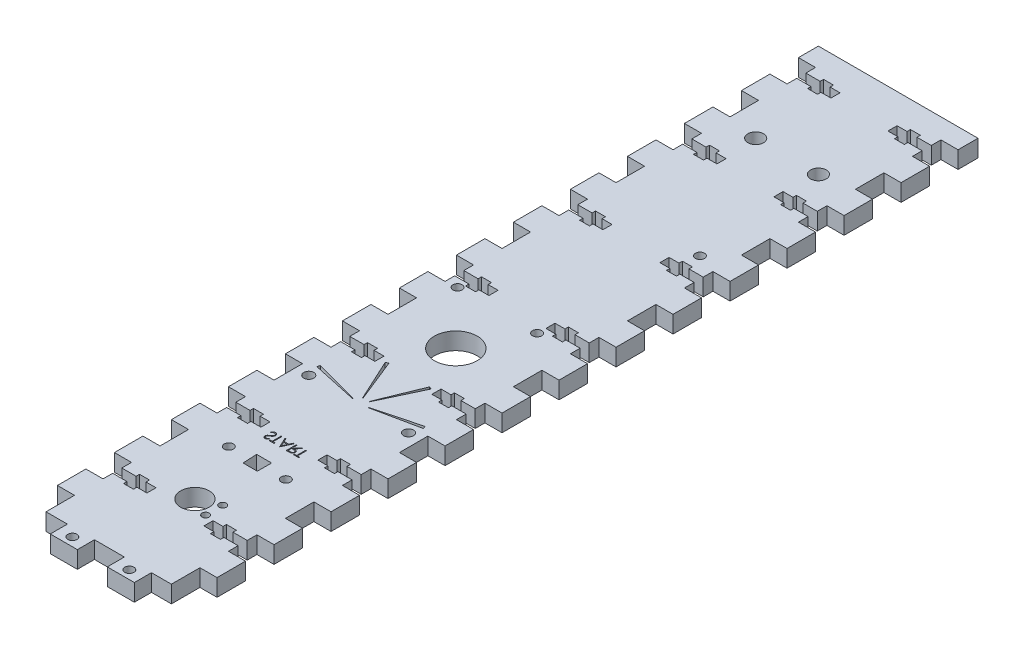
SolidWorks part; units mm, degrees
ref_plane "Plan de face" through (0, 0, 0) normal (0, 0, 1) x (1, 0, 0)
ref_plane "Plan de dessus" through (0, 0, 0) normal (0, 1, 0) x (1, 0, 0)
ref_plane "Plan de droite" through (0, 0, 0) normal (1, 0, 0) x (0, 0, -1)
sketch "Sketch1" plane through (0, 0, 0) normal (0, 0, 1) x (1, 0, 0)
  line L1 (-85.7436, 30.1282) -> (-29.7436, 30.1282)
  line L2 (-85.7436, 30.1282) -> (-85.7436, 24.1282)
  line L3 (-85.7436, 24.1282) -> (-29.7436, 24.1282)
  line L4 (-29.7436, 30.1282) -> (-29.7436, 24.1282)
  dimension "D1" = 56
  dimension "D2" = 6
extrude "Boss-Extrude1" add sketch "Sketch1" along normal blind 277
sketch "Sketch3" plane through (0, 30.1282, 0) normal (0, 1, 0) x (1, 0, 0)
  line L0 (-85.7436, -277) -> (-79.7436, -277)
  line L1 (-29.7436, -277) -> (-85.7436, -277) construction
  line L2 (-29.7436, 0) -> (-85.7436, 0) construction
  line L3 (-57.7436, 0) -> (-57.7436, -277) construction
  line L4 (-29.7436, -277) -> (-35.7436, -277)
  line L5 (-29.7436, -277) -> (-29.7436, -267)
  line L6 (-29.7436, -267) -> (-35.7436, -267)
  line L7 (-35.7436, -277) -> (-35.7436, -267)
  line L8 (-85.7436, -277) -> (-85.7436, -267)
  line L9 (-85.7436, -267) -> (-79.7436, -267)
  line L10 (-79.7436, -277) -> (-79.7436, -267)
  line L11 (-85.7436, -257) -> (-79.7436, -257)
  line L12 (-79.7436, -257) -> (-79.7436, -247)
  line L13 (-85.7436, -247) -> (-79.7436, -247)
  line L14 (-85.7436, -257) -> (-85.7436, -247)
  line L15 (-29.7436, -257) -> (-29.7436, -247)
  line L16 (-29.7436, -257) -> (-35.7436, -257)
  line L17 (-35.7436, -257) -> (-35.7436, -247)
  line L18 (-29.7436, -247) -> (-35.7436, -247)
  line L19 (-85.7436, -237) -> (-79.7436, -237)
  line L20 (-79.7436, -237) -> (-79.7436, -227)
  line L21 (-85.7436, -227) -> (-79.7436, -227)
  line L22 (-85.7436, -237) -> (-85.7436, -227)
  line L23 (-29.7436, -237) -> (-29.7436, -227)
  line L24 (-29.7436, -237) -> (-35.7436, -237)
  line L25 (-35.7436, -237) -> (-35.7436, -227)
  line L26 (-29.7436, -227) -> (-35.7436, -227)
  line L27 (-85.7436, -217) -> (-79.7436, -217)
  line L28 (-79.7436, -217) -> (-79.7436, -207)
  line L29 (-85.7436, -207) -> (-79.7436, -207)
  line L30 (-85.7436, -217) -> (-85.7436, -207)
  line L31 (-29.7436, -217) -> (-29.7436, -207)
  line L32 (-29.7436, -217) -> (-35.7436, -217)
  line L33 (-35.7436, -217) -> (-35.7436, -207)
  line L34 (-29.7436, -207) -> (-35.7436, -207)
  line L35 (-85.7436, -197) -> (-79.7436, -197)
  line L36 (-79.7436, -197) -> (-79.7436, -187)
  line L37 (-85.7436, -187) -> (-79.7436, -187)
  line L38 (-85.7436, -197) -> (-85.7436, -187)
  line L39 (-29.7436, -197) -> (-29.7436, -187)
  line L40 (-29.7436, -197) -> (-35.7436, -197)
  line L41 (-35.7436, -197) -> (-35.7436, -187)
  line L42 (-29.7436, -187) -> (-35.7436, -187)
  line L43 (-85.7436, -177) -> (-79.7436, -177)
  line L44 (-79.7436, -177) -> (-79.7436, -167)
  line L45 (-85.7436, -167) -> (-79.7436, -167)
  line L46 (-85.7436, -177) -> (-85.7436, -167)
  line L47 (-29.7436, -177) -> (-29.7436, -167)
  line L48 (-29.7436, -177) -> (-35.7436, -177)
  line L49 (-35.7436, -177) -> (-35.7436, -167)
  line L50 (-29.7436, -167) -> (-35.7436, -167)
  line L51 (-85.7436, -157) -> (-79.7436, -157)
  line L52 (-79.7436, -157) -> (-79.7436, -147)
  line L53 (-85.7436, -147) -> (-79.7436, -147)
  line L54 (-85.7436, -157) -> (-85.7436, -147)
  line L55 (-29.7436, -157) -> (-29.7436, -147)
  line L56 (-29.7436, -157) -> (-35.7436, -157)
  line L57 (-35.7436, -157) -> (-35.7436, -147)
  line L58 (-29.7436, -147) -> (-35.7436, -147)
  line L59 (-85.7436, -137) -> (-79.7436, -137)
  line L60 (-79.7436, -137) -> (-79.7436, -127)
  line L61 (-85.7436, -127) -> (-79.7436, -127)
  line L62 (-85.7436, -137) -> (-85.7436, -127)
  line L63 (-29.7436, -137) -> (-29.7436, -127)
  line L64 (-29.7436, -137) -> (-35.7436, -137)
  line L65 (-35.7436, -137) -> (-35.7436, -127)
  line L66 (-29.7436, -127) -> (-35.7436, -127)
  line L67 (-85.7436, -117) -> (-79.7436, -117)
  line L68 (-79.7436, -117) -> (-79.7436, -107)
  line L69 (-85.7436, -107) -> (-79.7436, -107)
  line L70 (-85.7436, -117) -> (-85.7436, -107)
  line L71 (-29.7436, -117) -> (-29.7436, -107)
  line L72 (-29.7436, -117) -> (-35.7436, -117)
  line L73 (-35.7436, -117) -> (-35.7436, -107)
  line L74 (-29.7436, -107) -> (-35.7436, -107)
  line L75 (-85.7436, -97) -> (-79.7436, -97)
  line L76 (-79.7436, -97) -> (-79.7436, -87)
  line L77 (-85.7436, -87) -> (-79.7436, -87)
  line L78 (-85.7436, -97) -> (-85.7436, -87)
  line L79 (-29.7436, -97) -> (-29.7436, -87)
  line L80 (-29.7436, -97) -> (-35.7436, -97)
  line L81 (-35.7436, -97) -> (-35.7436, -87)
  line L82 (-29.7436, -87) -> (-35.7436, -87)
  line L83 (-85.7436, -77) -> (-79.7436, -77)
  line L84 (-79.7436, -77) -> (-79.7436, -67)
  line L85 (-85.7436, -67) -> (-79.7436, -67)
  line L86 (-85.7436, -77) -> (-85.7436, -67)
  line L87 (-29.7436, -77) -> (-29.7436, -67)
  line L88 (-29.7436, -77) -> (-35.7436, -77)
  line L89 (-35.7436, -77) -> (-35.7436, -67)
  line L90 (-29.7436, -67) -> (-35.7436, -67)
  line L91 (-85.7436, -57) -> (-79.7436, -57)
  line L92 (-79.7436, -57) -> (-79.7436, -47)
  line L93 (-85.7436, -47) -> (-79.7436, -47)
  line L94 (-85.7436, -57) -> (-85.7436, -47)
  line L95 (-29.7436, -57) -> (-29.7436, -47)
  line L96 (-29.7436, -57) -> (-35.7436, -57)
  line L97 (-35.7436, -57) -> (-35.7436, -47)
  line L98 (-29.7436, -47) -> (-35.7436, -47)
  line L99 (-85.7436, -37) -> (-79.7436, -37)
  line L100 (-79.7436, -37) -> (-79.7436, -27)
  line L101 (-85.7436, -27) -> (-79.7436, -27)
  line L102 (-85.7436, -37) -> (-85.7436, -27)
  line L103 (-29.7436, -37) -> (-29.7436, -27)
  line L104 (-29.7436, -37) -> (-35.7436, -37)
  line L105 (-35.7436, -37) -> (-35.7436, -27)
  line L106 (-29.7436, -27) -> (-35.7436, -27)
  line L107 (-85.7436, -17) -> (-79.7436, -17)
  line L108 (-79.7436, -17) -> (-79.7436, -7)
  line L109 (-85.7436, -7) -> (-79.7436, -7)
  line L110 (-85.7436, -17) -> (-85.7436, -7)
  line L111 (-29.7436, -17) -> (-29.7436, -7)
  line L112 (-29.7436, -17) -> (-35.7436, -17)
  line L113 (-35.7436, -17) -> (-35.7436, -7)
  line L114 (-29.7436, -7) -> (-35.7436, -7)
  dimension "D1" = 6
  dimension "D2" = 10
  dimension "D3" = 14
extrude "Cut-Extrude1" cut sketch "Sketch3" against normal through all
sketch "Sketch6" plane through (0, 0, 277) normal (0, 0, 1) x (1, 0, 0)
  line L0 (-35.7436, 30.1282) -> (-79.7436, 30.1282) construction
  line L1 (-72.2436, 30.1282) -> (-62.7436, 30.1282)
  line L2 (-72.2436, 30.1282) -> (-72.2436, 24.1282)
  line L3 (-72.2436, 24.1282) -> (-62.7436, 24.1282)
  line L4 (-62.7436, 30.1282) -> (-62.7436, 24.1282)
  line L5 (-79.7436, 24.1282) -> (-35.7436, 24.1282) construction
  line L6 (-79.7436, 24.1282) -> (-79.7436, 30.1282) construction
  line L7 (-52.2436, 30.1282) -> (-52.2436, 24.1282)
  line L8 (-52.2436, 30.1282) -> (-42.7436, 30.1282)
  line L9 (-42.7436, 30.1282) -> (-42.7436, 24.1282)
  line L10 (-52.2436, 24.1282) -> (-42.7436, 24.1282)
  dimension "D1" = 7.5
  dimension "D2" = 9.5
  dimension "D3" = 2
extrude "Boss-Extrude2" add sketch "Sketch6" along normal blind 6
sketch "Sketch9" plane through (-35.7436, 0, 0) normal (1, 0, 0) x (0, 0, -1)
  line L0 (-257, 24.1282) -> (-247, 30.1282) construction
  line L1 (-247, 24.1282) -> (-257, 24.1282) construction
  line L2 (-250.4, 30.1282) -> (-253.6, 30.1282)
  line L3 (-250.4, 30.1282) -> (-250.4, 24.1282)
  line L4 (-250.4, 24.1282) -> (-253.6, 24.1282)
  line L5 (-253.6, 30.1282) -> (-253.6, 24.1282)
  line L6 (-250.4, 30.1282) -> (-253.6, 24.1282) construction
  line L7 (-250.4, 24.1282) -> (-253.6, 30.1282) construction
  line L8 (-210.4, 30.1282) -> (-210.4, 24.1282)
  line L9 (-210.4, 30.1282) -> (-213.6, 30.1282)
  line L10 (-213.6, 30.1282) -> (-213.6, 24.1282)
  line L11 (-210.4, 24.1282) -> (-213.6, 24.1282)
  line L12 (-170.4, 30.1282) -> (-170.4, 24.1282)
  line L13 (-170.4, 30.1282) -> (-173.6, 30.1282)
  line L14 (-173.6, 30.1282) -> (-173.6, 24.1282)
  line L15 (-170.4, 24.1282) -> (-173.6, 24.1282)
  line L16 (-130.4, 30.1282) -> (-130.4, 24.1282)
  line L17 (-130.4, 30.1282) -> (-133.6, 30.1282)
  line L18 (-133.6, 30.1282) -> (-133.6, 24.1282)
  line L19 (-130.4, 24.1282) -> (-133.6, 24.1282)
  line L20 (-90.4, 30.1282) -> (-90.4, 24.1282)
  line L21 (-90.4, 30.1282) -> (-93.6, 30.1282)
  line L22 (-93.6, 30.1282) -> (-93.6, 24.1282)
  line L23 (-90.4, 24.1282) -> (-93.6, 24.1282)
  line L24 (-50.4, 30.1282) -> (-50.4, 24.1282)
  line L25 (-50.4, 30.1282) -> (-53.6, 30.1282)
  line L26 (-53.6, 30.1282) -> (-53.6, 24.1282)
  line L27 (-50.4, 24.1282) -> (-53.6, 24.1282)
  line L28 (-10.4, 30.1282) -> (-10.4, 24.1282)
  line L29 (-10.4, 30.1282) -> (-13.6, 30.1282)
  line L30 (-13.6, 30.1282) -> (-13.6, 24.1282)
  line L31 (-10.4, 24.1282) -> (-13.6, 24.1282)
  point P4 (-252, 27.1282)
  dimension "D1" = 3.2
  dimension "D2" = 7
extrude "Cut-Extrude2" cut sketch "Sketch9" against normal blind 12
sketch "Sketch10" plane through (-79.7436, 0, 0) normal (-1, 0, 0) x (0, 0, 1)
  line L0 (257, 30.1282) -> (247, 24.1282) construction
  line L1 (257, 30.1282) -> (247, 30.1282) construction
  line L2 (250.4, 24.1282) -> (253.6, 24.1282)
  line L3 (250.4, 24.1282) -> (250.4, 30.1282)
  line L4 (250.4, 30.1282) -> (253.6, 30.1282)
  line L5 (253.6, 24.1282) -> (253.6, 30.1282)
  line L6 (250.4, 24.1282) -> (253.6, 30.1282) construction
  line L7 (250.4, 30.1282) -> (253.6, 24.1282) construction
  line L8 (210.4, 24.1282) -> (210.4, 30.1282)
  line L9 (210.4, 24.1282) -> (213.6, 24.1282)
  line L10 (213.6, 24.1282) -> (213.6, 30.1282)
  line L11 (210.4, 30.1282) -> (213.6, 30.1282)
  line L12 (170.4, 24.1282) -> (170.4, 30.1282)
  line L13 (170.4, 24.1282) -> (173.6, 24.1282)
  line L14 (173.6, 24.1282) -> (173.6, 30.1282)
  line L15 (170.4, 30.1282) -> (173.6, 30.1282)
  line L16 (130.4, 24.1282) -> (130.4, 30.1282)
  line L17 (130.4, 24.1282) -> (133.6, 24.1282)
  line L18 (133.6, 24.1282) -> (133.6, 30.1282)
  line L19 (130.4, 30.1282) -> (133.6, 30.1282)
  line L20 (90.4, 24.1282) -> (90.4, 30.1282)
  line L21 (90.4, 24.1282) -> (93.6, 24.1282)
  line L22 (93.6, 24.1282) -> (93.6, 30.1282)
  line L23 (90.4, 30.1282) -> (93.6, 30.1282)
  line L24 (50.4, 24.1282) -> (50.4, 30.1282)
  line L25 (50.4, 24.1282) -> (53.6, 24.1282)
  line L26 (53.6, 24.1282) -> (53.6, 30.1282)
  line L27 (50.4, 30.1282) -> (53.6, 30.1282)
  line L28 (10.4, 24.1282) -> (10.4, 30.1282)
  line L29 (10.4, 24.1282) -> (13.6, 24.1282)
  line L30 (13.6, 24.1282) -> (13.6, 30.1282)
  line L31 (10.4, 30.1282) -> (13.6, 30.1282)
  point P4 (252, 27.1282)
  dimension "D1" = 3.2
  dimension "D2" = 7
extrude "Cut-Extrude3" cut sketch "Sketch10" against normal blind 12
sketch "Sketch11" plane through (0, 24.1282, 0) normal (0, -1, 0) x (1, 0, 0)
  line L0 (-57.7436, 277) -> (-57.7436, 0) construction
  line L1 (-74.7436, 254.8) -> (-71.2436, 254.8)
  line L2 (-74.7436, 254.8) -> (-74.7436, 249.2)
  line L3 (-74.7436, 249.2) -> (-71.2436, 249.2)
  line L4 (-71.2436, 254.8) -> (-71.2436, 249.2)
  line L6 (-85.7436, 0) -> (-29.7436, 0) construction
  line L8 (-79.7436, 257) -> (-79.7436, 253.6) construction
  line L9 (-40.7436, 249.2) -> (-44.2436, 249.2)
  line L10 (-44.2436, 254.8) -> (-44.2436, 249.2)
  line L11 (-40.7436, 254.8) -> (-44.2436, 254.8)
  line L12 (-40.7436, 254.8) -> (-40.7436, 249.2)
  line L13 (-74.7436, 214.8) -> (-74.7436, 209.2)
  line L14 (-74.7436, 214.8) -> (-71.2436, 214.8)
  line L15 (-71.2436, 214.8) -> (-71.2436, 209.2)
  line L16 (-74.7436, 209.2) -> (-71.2436, 209.2)
  line L17 (-40.7436, 209.2) -> (-44.2436, 209.2)
  line L18 (-44.2436, 214.8) -> (-44.2436, 209.2)
  line L19 (-40.7436, 214.8) -> (-44.2436, 214.8)
  line L20 (-40.7436, 214.8) -> (-40.7436, 209.2)
  line L21 (-74.7436, 174.8) -> (-74.7436, 169.2)
  line L22 (-74.7436, 174.8) -> (-71.2436, 174.8)
  line L23 (-71.2436, 174.8) -> (-71.2436, 169.2)
  line L24 (-74.7436, 169.2) -> (-71.2436, 169.2)
  line L25 (-40.7436, 169.2) -> (-44.2436, 169.2)
  line L26 (-44.2436, 174.8) -> (-44.2436, 169.2)
  line L27 (-40.7436, 174.8) -> (-44.2436, 174.8)
  line L28 (-40.7436, 174.8) -> (-40.7436, 169.2)
  line L29 (-74.7436, 134.8) -> (-74.7436, 129.2)
  line L30 (-74.7436, 134.8) -> (-71.2436, 134.8)
  line L31 (-71.2436, 134.8) -> (-71.2436, 129.2)
  line L32 (-74.7436, 129.2) -> (-71.2436, 129.2)
  line L33 (-40.7436, 129.2) -> (-44.2436, 129.2)
  line L34 (-44.2436, 134.8) -> (-44.2436, 129.2)
  line L35 (-40.7436, 134.8) -> (-44.2436, 134.8)
  line L36 (-40.7436, 134.8) -> (-40.7436, 129.2)
  line L37 (-74.7436, 94.8) -> (-74.7436, 89.2)
  line L38 (-74.7436, 94.8) -> (-71.2436, 94.8)
  line L39 (-71.2436, 94.8) -> (-71.2436, 89.2)
  line L40 (-74.7436, 89.2) -> (-71.2436, 89.2)
  line L41 (-40.7436, 89.2) -> (-44.2436, 89.2)
  line L42 (-44.2436, 94.8) -> (-44.2436, 89.2)
  line L43 (-40.7436, 94.8) -> (-44.2436, 94.8)
  line L44 (-40.7436, 94.8) -> (-40.7436, 89.2)
  line L45 (-74.7436, 54.8) -> (-74.7436, 49.2)
  line L46 (-74.7436, 54.8) -> (-71.2436, 54.8)
  line L47 (-71.2436, 54.8) -> (-71.2436, 49.2)
  line L48 (-74.7436, 49.2) -> (-71.2436, 49.2)
  line L49 (-40.7436, 49.2) -> (-44.2436, 49.2)
  line L50 (-44.2436, 54.8) -> (-44.2436, 49.2)
  line L51 (-40.7436, 54.8) -> (-44.2436, 54.8)
  line L52 (-40.7436, 54.8) -> (-40.7436, 49.2)
  line L53 (-74.7436, 14.8) -> (-74.7436, 9.2)
  line L54 (-74.7436, 14.8) -> (-71.2436, 14.8)
  line L55 (-71.2436, 14.8) -> (-71.2436, 9.2)
  line L56 (-74.7436, 9.2) -> (-71.2436, 9.2)
  line L57 (-40.7436, 9.2) -> (-44.2436, 9.2)
  line L58 (-44.2436, 14.8) -> (-44.2436, 9.2)
  line L59 (-40.7436, 14.8) -> (-44.2436, 14.8)
  line L60 (-40.7436, 14.8) -> (-40.7436, 9.2)
  line L61 (-47.7436, 250.4) -> (-47.7436, 253.6) construction
  point P6 (-44.2436, 252)
  point P67 (-47.7436, 252)
  dimension "D1" = 5.6
  dimension "D3" = 5
  dimension "D4" = 3.5
  dimension "D5" = 7
extrude "Cut-Extrude4" cut sketch "Sketch11" against normal blind 12
sketch "Sketch12" plane through (0, 24.1282, 0) normal (0, -1, 0) x (1, 0, 0)
  line L2 (-42.7436, 283) -> (-52.2436, 283) construction
  line L3 (-62.7436, 283) -> (-72.2436, 283) construction
  line L5 (-42.7436, 283) -> (-42.7436, 277) construction
  line L7 (-72.2436, 283) -> (-72.2436, 277) construction
  circle A0 centre (-67.4936, 280) radius 1.6
  circle A1 centre (-47.4936, 280) radius 1.6
  point P6 (-47.4936, 283)
  point P14 (-67.4936, 283)
  point P15 (-42.7436, 280)
  point P18 (-72.2436, 280)
  dimension "D1" = 3.2
  dimension "D2" = 3.2
extrude "Cut-Extrude5" cut sketch "Sketch12" against normal blind 12
sketch "Sketch14" plane through (0, 24.1282, 0) normal (0, -1, 0) x (1, 0, 0)
  line L0 (-57.7436, 0) -> (-57.7436, 54.5316) construction
  line L1 (-85.7436, 0) -> (-29.7436, 0) construction
  circle A0 centre (-68.7436, 39) radius 2.75
  circle A1 centre (-46.7436, 39) radius 2.75
  point P10 (-57.7436, 0)
  dimension "D1" = 5.5
  dimension "D2" = 11
  dimension "D3" = 39
extrude "Cut-Extrude6" cut sketch "Sketch14" against normal through all
sketch "Sketch15" plane through (0, 24.1282, 0) normal (0, -1, 0) x (1, 0, 0)
  line L1 (-75.7436, 136.6) -> (-47.8436, 136.6) construction
  line L2 (-75.7436, 136.6) -> (-75.7436, 84.5) construction
  line L3 (-75.7436, 84.5) -> (-47.8436, 84.5) construction
  line L4 (-47.8436, 136.6) -> (-47.8436, 84.5) construction
  line L5 (-47.8436, 136.6) -> (-42.7936, 136.6) construction
  line L6 (-47.8436, 136.6) -> (-47.8436, 84.5) construction
  line L7 (-47.8436, 84.5) -> (-42.7936, 84.5) construction
  line L8 (-42.7936, 136.6) -> (-42.7936, 84.5) construction
  line L9 (-52.2436, 277) -> (-62.7436, 277) construction
  line L10 (-85.7436, 107) -> (-85.7436, 97) construction
  circle A0 centre (-75.7436, 136.6) radius 1.6
  circle A1 centre (-47.8436, 136.6) radius 1.6
  circle A2 centre (-42.7936, 84.5) radius 1.6
  circle A3 centre (-57.4936, 155.4617) radius 7.5
  point P17 (-57.4936, 277)
  dimension "D3" = 3.2
  dimension "D4" = 3.2
  dimension "D6" = 3.2
  dimension "D7" = 15
  dimension "D1" = 27.9
  dimension "D2" = 52.1
  dimension "D5" = 5.05
  dimension "D8" = 17.5
  dimension "D9" = 10
extrude "Cut-Extrude7" cut sketch "Sketch15" against normal through all
sketch "Sketch16" plane through (0, 24.1282, 0) normal (0, -1, 0) x (1, 0, 0)
  line L0 (-35.7436, 227) -> (-35.7436, 237) construction
  line L1 (-50.7436, 250) -> (-50.7436, 244) construction
  line L2 (-52.2436, 277) -> (-62.7436, 277) construction
  line L3 (-42.7436, 277) -> (-35.7436, 277) construction
  circle A0 centre (-50.7436, 250) radius 1.25
  circle A1 centre (-50.7436, 244) radius 1.25
  circle A2 centre (-57.4936, 247) radius 5
  point P8 (-50.7436, 247)
  point P14 (-57.4936, 277)
  dimension "D1" = 2.5
  dimension "D2" = 2.5
  dimension "D5" = 10
  dimension "D3" = 6
  dimension "D4" = 15
  dimension "D6" = 30
extrude "Cut-Extrude8" cut sketch "Sketch16" against normal through all
sketch "Sketch17" plane through (0, 24.1282, 0) normal (0, -1, 0) x (1, 0, 0)
  line L0 (-67.4936, 225.1039) -> (-47.4936, 225.1039) construction
  line L1 (-62.7436, 277) -> (-52.2436, 277) construction
  line L2 (-57.4936, 235.1039) -> (-57.4936, 220.1039) construction
  line L3 (-59.9936, 227.6039) -> (-54.9936, 227.6039)
  line L6 (-54.9936, 227.6039) -> (-54.9936, 222.6039)
  line L7 (-59.9936, 227.6039) -> (-60.2436, 222.6039)
  line L8 (-60.2436, 222.6039) -> (-54.9936, 222.6039)
  line L9 (-67.7436, 210.4) -> (-67.7436, 213.6) construction
  circle A2 centre (-67.4936, 225.1039) radius 1.6
  circle A3 centre (-47.4936, 225.1039) radius 1.6
  text T0 "START"
  point P8 (-57.4936, 277)
  point P9 (-57.4936, 227.6039)
  point P10 (-57.4936, 227.6039)
  dimension "D1" = 3.2
  dimension "D2" = 15
  dimension "D3" = 3.2
  dimension "D8" = 7.5
  dimension "D4" = 20
  dimension "D5" = 5
  dimension "D6" = 5
  dimension "D7" = 3
extrude "Cut-Extrude9" cut sketch "Sketch17" against normal blind 10
sketch "Sketch18" plane through (0, 24.1282, 0) normal (0, -1, 0) x (1, 0, 0)
  line L0 (-75.1186, 189.4311) -> (-40.1186, 189.4311) construction
  line L1 (-60.2436, 222.6039) -> (-54.9936, 222.6039) construction
  line L2 (-57.6186, 189.4311) -> (-39.1569, 184.5495) construction
  line L3 (-57.6186, 189.4311) -> (-76.0476, 184.4278) construction
  line L4 (-57.6186, 189.4311) -> (-65.6318, 172.0976) construction
  line L5 (-57.6186, 189.4311) -> (-49.4912, 172.1508) construction
  line L6 (125.2591, 485.958) -> (158.0404, 485.958) construction
  line L9 (-863.7024, 468.9667) -> (-829.7978, 468.9667) construction
  line L10 (-57.6186, 189.4311) -> (-65.6318, 172.0976)
  line L11 (-65.6318, 172.0976) -> (-64.7135, 171.7019)
  line L12 (-64.7135, 171.7019) -> (-57.6186, 189.4311)
  line L13 (-57.6186, 189.4311) -> (-49.4912, 172.1508)
  line L14 (-49.4912, 172.1508) -> (-50.4069, 171.7491)
  line L15 (-50.4069, 171.7491) -> (-57.6186, 189.4311)
  line L16 (-57.6186, 189.4311) -> (-39.1569, 184.5495)
  line L17 (-39.1569, 184.5495) -> (-38.9013, 185.5163)
  line L18 (-38.9013, 185.5163) -> (-57.6186, 189.4311)
  line L19 (-57.6186, 189.4311) -> (-76.0476, 184.4278)
  line L20 (-76.0476, 184.4278) -> (-76.3096, 185.3929)
  line L21 (-76.3096, 185.3929) -> (-57.6186, 189.4311)
  circle A0 centre (-75.1186, 189.4311) radius 1.75
  circle A1 centre (-40.1186, 189.4311) radius 1.75
  arc A2 (-76.0476, 184.4278) -> (-39.1569, 184.5495) centre (-57.6186, 189.4311) ccw construction
  arc A3 (-75.1186, 189.4311) -> (-40.1186, 189.4311) centre (-57.6186, 189.4311) cw construction
  circle A4 centre (-57.6186, 189.4311) radius 2.8572
  point P4 (-57.6186, 189.4311)
  point P7 (-57.6186, 222.6039)
  dimension "D1" = 3.5
  dimension "D2" = 3.5
  dimension "D3" = 35
  dimension "D4" = 50
  dimension "D5" = 50
  dimension "D6" = 150
  dimension "D7" = 1
  dimension "D8" = 1
  dimension "D9" = 1
  dimension "D10" = 1
extrude "Cut-Extrude10" cut sketch "Sketch18" against normal through all both and the other way through all
equation "\"3.é\"=2.2"
